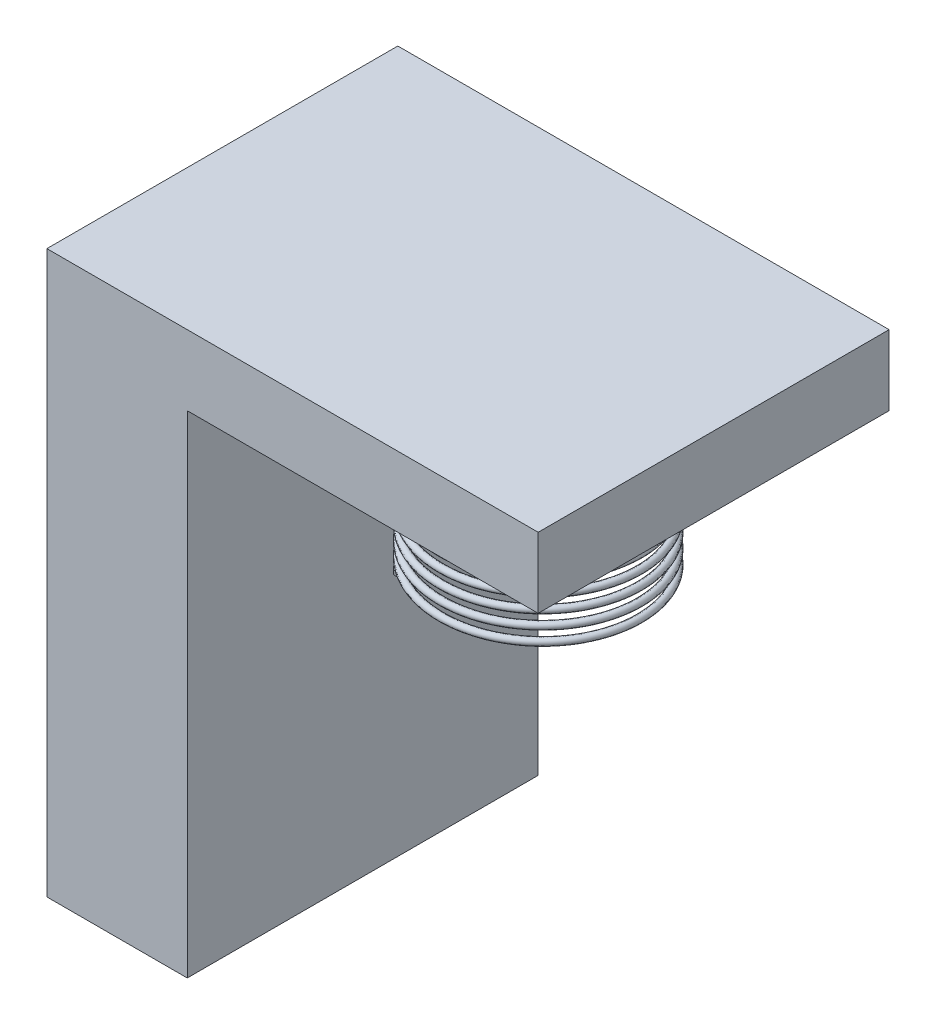
SolidWorks part; units mm, degrees
ref_plane "Front Plane" through (0, 0, 0) normal (0, 0, 1) x (1, 0, 0)
ref_plane "Top Plane" through (0, 0, 0) normal (0, 1, 0) x (1, 0, 0)
ref_plane "Right Plane" through (0, 0, 0) normal (1, 0, 0) x (0, 0, -1)
sketch "Sketch1" plane through (0, 0, 0) normal (0, 1, 0) x (1, 0, 0)
  line L1 (10, -25) -> (-10, -25)
  line L2 (10, -25) -> (10, 25)
  line L3 (10, 25) -> (-10, 25)
  line L4 (-10, -25) -> (-10, 25)
  line L5 (10, -25) -> (-10, 25) construction
  line L6 (10, 25) -> (-10, -25) construction
  point P0 (0, 0)
  dimension "D1" = 50
  dimension "D2" = 20
extrude "Boss-Extrude1" add sketch "Sketch1" along normal blind 80
sketch "Sketch2" plane through (10, 0, 0) normal (1, 0, 0) x (0, 0, -1)
  line L0 (25, 80) -> (25, 0) construction
  line L1 (-25, 80) -> (25, 80)
  line L2 (-25, 80) -> (-25, 70)
  line L3 (-25, 70) -> (25, 70)
  line L4 (25, 80) -> (25, 70)
  dimension "D1" = 10
extrude "Boss-Extrude2" add sketch "Sketch2" along normal blind 50
sketch "Sketch4" plane through (0, 70, 0) normal (0, -1, 0) x (1, 0, 0)
  line L0 (60, 25) -> (10, 25) construction
  line L1 (60, 25) -> (60, -25) construction
  circle A0 centre (35, 0) radius 14.095
  dimension "D1" = 25
  dimension "D2" = 25
curve "Helix/Spiral1" pitch 2 height 20 turns 10
sketch "Sketch8" plane through (0, 70, 0) normal (0, -1, 0) x (1, 0, 0)
  circle A0 centre (25.0333, 9.9667) radius 1.0358
  point P2 (0, 0)
sweep "Sweep1" add path "Helix/Spiral1" circular profile diameter 1 parameters "D3"=1
